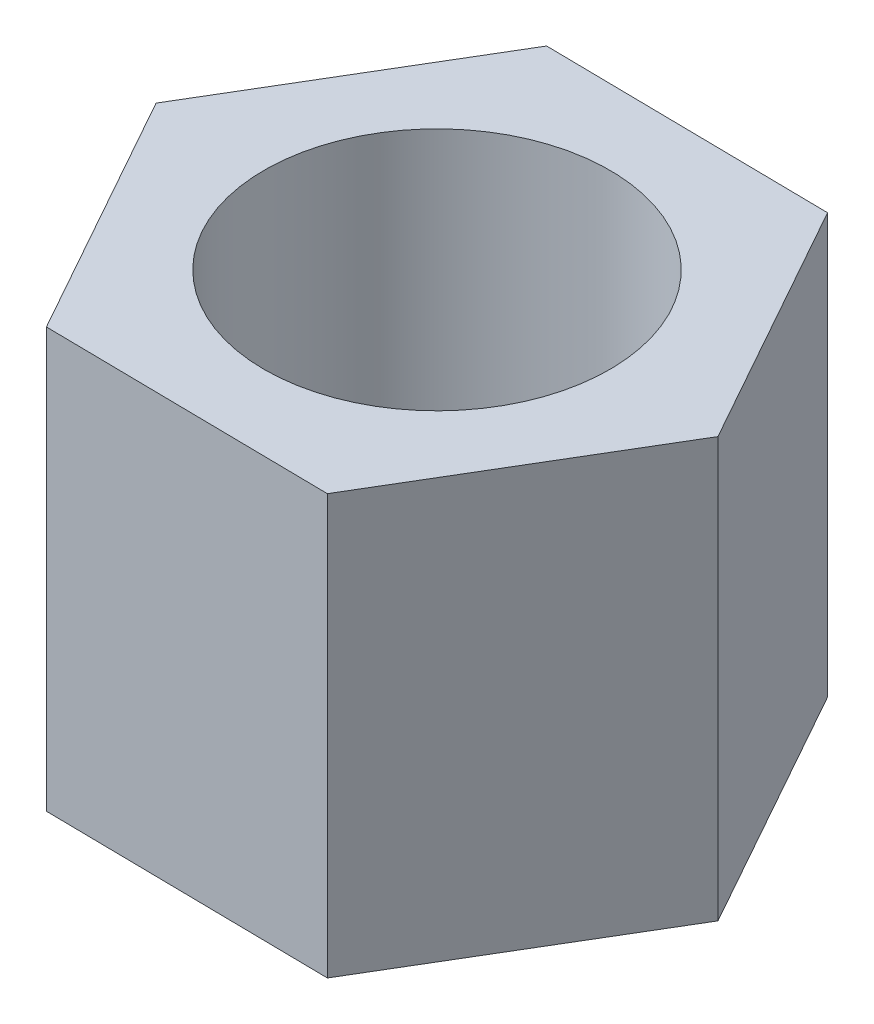
SolidWorks part; units mm, degrees
material "1.4000 (X6Cr13)"
ref_plane "正面" through (0, 0, 0) normal (0, 0, 1) x (1, 0, 0)
ref_plane "平面" through (0, 0, 0) normal (0, 1, 0) x (1, 0, 0)
ref_plane "右側面" through (0, 0, 0) normal (1, 0, 0) x (0, 0, -1)
sketch "ｽｹｯﾁ1" plane through (0, 0, 0) normal (0, 1, 0) x (1, 0, 0)
  line L1 (5.635, -10.0787) -> (11.5459, -0.1593)
  line L2 (11.5459, -0.1593) -> (5.9109, 9.9194)
  line L3 (5.9109, 9.9194) -> (-5.635, 10.0787)
  line L4 (-5.635, 10.0787) -> (-11.5459, 0.1593)
  line L5 (-11.5459, 0.1593) -> (-5.9109, -9.9194)
  line L6 (-5.9109, -9.9194) -> (5.635, -10.0787)
  circle A0 centre (0, 0) radius 10 construction
  dimension "D1" = 20
extrude "ﾎﾞｽ - 押し出し1" add sketch "ｽｹｯﾁ1" along normal blind 17
sketch "ｽｹｯﾁ2" plane through (0, 17, 0) normal (0, 1, 0) x (1, 0, 0)
  circle A0 centre (0, 0) radius 7
extrude "ｶｯﾄ - 押し出し1" cut sketch "ｽｹｯﾁ2" against normal blind 10
